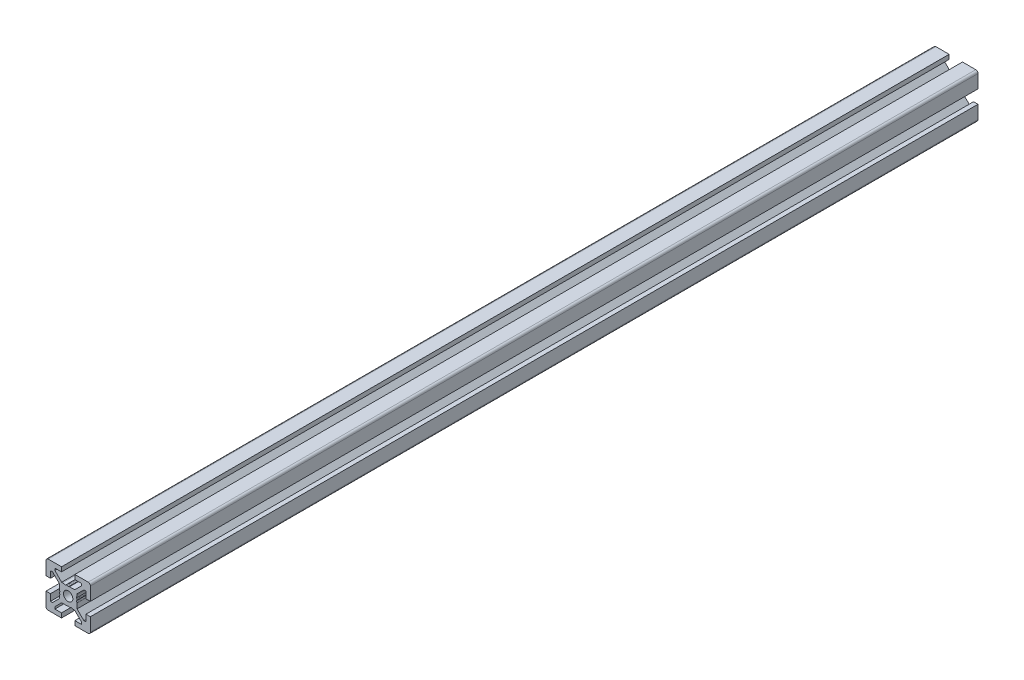
SolidWorks part; units mm, degrees
ref_plane "前基準面" through (0, 0, 0) normal (0, 0, 1) x (1, 0, 0)
ref_plane "上基準面" through (0, 0, 0) normal (0, 1, 0) x (1, 0, 0)
ref_plane "右基準面" through (0, 0, 0) normal (1, 0, 0) x (0, 0, -1)
ref_plane "平面1" through (0, 0, -2500) normal (0, 0, -1) x (-1, 0, 0)
sketch "草圖1" plane through (0, 0, -2500) normal (0, 0, -1) x (-1, 0, 0)
  line L0 (10, -3) -> (8, -3)
  line L1 (8, -3) -> (8, -6)
  line L2 (8, -6) -> (7.0607, -6)
  line L3 (7.0607, -6) -> (4, -2.9393)
  line L4 (4, -2.9393) -> (4, -2.5)
  line L5 (4, -2.5) -> (3.751, -1.2189)
  line L6 (3.751, -1.2189) -> (3.933, -0.9036)
  line L7 (3.933, -0.4036) -> (3.7, 0)
  line L8 (3.7, 0) -> (3.933, 0.4036)
  line L9 (4, 0.6536) -> (4, 2.9393)
  line L10 (4, 2.9393) -> (7.0607, 6)
  line L11 (7.0607, 6) -> (8, 6)
  line L12 (8, 6) -> (8, 3)
  line L13 (8, 3) -> (10, 3)
  line L14 (10, 3) -> (10, 9)
  line L15 (9, 10) -> (3, 10)
  line L16 (3, 10) -> (3, 8)
  line L17 (3, 8) -> (6, 8)
  line L18 (6, 8) -> (6, 7.0607)
  line L19 (6, 7.0607) -> (2.9393, 4)
  line L20 (2.9393, 4) -> (2.5, 4)
  line L21 (2.5, 4) -> (1.2189, 3.751)
  line L22 (1.2189, 3.751) -> (0.9036, 3.933)
  line L23 (0.4036, 3.933) -> (0, 3.7)
  line L24 (0, 3.7) -> (-0.4036, 3.933)
  line L25 (-0.6536, 4) -> (-2.9393, 4)
  line L26 (-2.9393, 4) -> (-6, 7.0607)
  line L27 (-6, 7.0607) -> (-6, 8)
  line L28 (-6, 8) -> (-3, 8)
  line L29 (-3, 8) -> (-3, 10)
  line L30 (-3, 10) -> (-9, 10)
  line L31 (-10, 9) -> (-10, 3)
  line L32 (-10, 3) -> (-8, 3)
  line L33 (-8, 3) -> (-8, 6)
  line L34 (-8, 6) -> (-7.0607, 6)
  line L35 (-7.0607, 6) -> (-4, 2.9393)
  line L36 (-4, 2.9393) -> (-4, 2.5)
  line L37 (-4, 2.5) -> (-3.751, 1.2189)
  line L38 (-3.751, 1.2189) -> (-3.933, 0.9036)
  line L39 (-3.933, 0.4036) -> (-3.7, 0)
  line L40 (-3.7, 0) -> (-3.933, -0.4036)
  line L41 (-4, -0.6536) -> (-4, -2.9393)
  line L42 (-4, -2.9393) -> (-7.0607, -6)
  line L43 (-7.0607, -6) -> (-8, -6)
  line L44 (-8, -6) -> (-8, -3)
  line L45 (-8, -3) -> (-10, -3)
  line L46 (-10, -3) -> (-10, -9)
  line L47 (-9, -10) -> (-3, -10)
  line L48 (-3, -10) -> (-3, -8)
  line L49 (-3, -8) -> (-6, -8)
  line L50 (-6, -8) -> (-6, -7.0607)
  line L51 (-6, -7.0607) -> (-2.9393, -4)
  line L52 (-2.9393, -4) -> (-2.5, -4)
  line L53 (-2.5, -4) -> (-1.2189, -3.751)
  line L54 (-1.2189, -3.751) -> (-0.9036, -3.933)
  line L55 (-0.4036, -3.933) -> (0, -3.7)
  line L56 (0, -3.7) -> (0.4036, -3.933)
  line L57 (0.6536, -4) -> (2.9393, -4)
  line L58 (2.9393, -4) -> (6, -7.0607)
  line L59 (6, -7.0607) -> (6, -8)
  line L60 (6, -8) -> (3, -8)
  line L61 (3, -8) -> (3, -10)
  line L62 (3, -10) -> (9, -10)
  line L63 (10, -9) -> (10, -3)
  circle A0 centre (0, 0) radius 2.1
  arc A1 (3.933, -0.9036) -> (3.933, -0.4036) centre (3.5, -0.6536) ccw
  arc A2 (3.933, 0.4036) -> (4, 0.6536) centre (3.5, 0.6536) ccw
  arc A3 (10, 9) -> (9, 10) centre (9, 9) ccw
  arc A4 (0.9036, 3.933) -> (0.4036, 3.933) centre (0.6536, 3.5) ccw
  arc A5 (-0.4036, 3.933) -> (-0.6536, 4) centre (-0.6536, 3.5) ccw
  arc A6 (-9, 10) -> (-10, 9) centre (-9, 9) ccw
  arc A7 (-3.933, 0.9036) -> (-3.933, 0.4036) centre (-3.5, 0.6536) ccw
  arc A8 (-3.933, -0.4036) -> (-4, -0.6536) centre (-3.5, -0.6536) ccw
  arc A9 (-10, -9) -> (-9, -10) centre (-9, -9) ccw
  arc A10 (-0.9036, -3.933) -> (-0.4036, -3.933) centre (-0.6536, -3.5) ccw
  arc A11 (0.4036, -3.933) -> (0.6536, -4) centre (0.6536, -3.5) ccw
  arc A12 (9, -10) -> (10, -9) centre (9, -9) ccw
extrude "填料-伸長1" add sketch "草圖1" against normal blind 400
